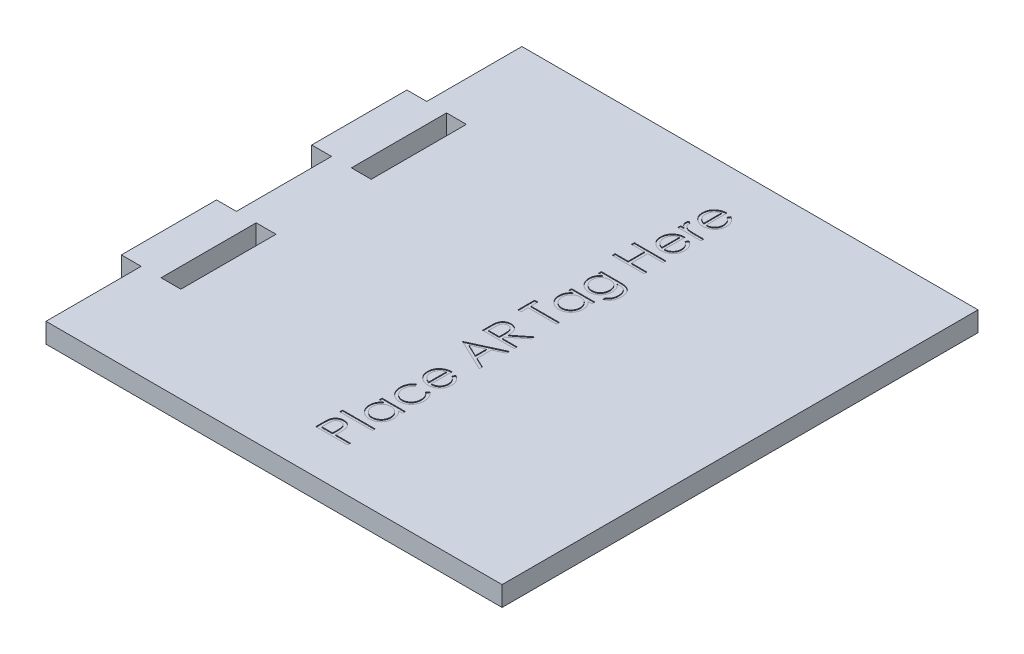
SolidWorks part; units mm, degrees
material "Pine"
ref_plane "Front Plane" through (0, 0, 0) normal (0, 0, 1) x (1, 0, 0)
ref_plane "Top Plane" through (0, 0, 0) normal (0, 1, 0) x (1, 0, 0)
ref_plane "Right Plane" through (0, 0, 0) normal (1, 0, 0) x (0, 0, -1)
sketch "Sketch1" plane through (0, 0, 0) normal (0, 1, 0) x (1, 0, 0)
  line L1 (-76.2, -76.2) -> (76.2, -76.2)
  line L2 (-76.2, -76.2) -> (-76.2, 76.2)
  line L3 (-76.2, 76.2) -> (76.2, 76.2)
  line L4 (76.2, -76.2) -> (76.2, 76.2)
  line L5 (-76.2, -76.2) -> (76.2, 76.2) construction
  line L6 (-76.2, 76.2) -> (76.2, -76.2) construction
  point P0 (0, 0)
  dimension "D1" = 152.4
  dimension "D2" = 152.4
extrude "Boss-Extrude1" add sketch "Sketch1" along normal blind 6.35
sketch "Sketch2" plane through (0, 6.35, 0) normal (0, 1, 0) x (1, 0, 0)
  line L1 (-57.15, -45.72) -> (-63.5, -45.72)
  line L2 (-57.15, -45.72) -> (-57.15, -15.24)
  line L3 (-57.15, -15.24) -> (-63.5, -15.24)
  line L4 (-63.5, -45.72) -> (-63.5, -15.24)
  line L5 (-76.2, -76.2) -> (76.2, -76.2) construction
  line L6 (-57.15, 15.24) -> (-63.5, 15.24)
  line L7 (-57.15, 15.24) -> (-57.15, 45.72)
  line L8 (-57.15, 45.72) -> (-63.5, 45.72)
  line L9 (-63.5, 15.24) -> (-63.5, 45.72)
  line L10 (-76.2, 76.2) -> (-76.2, -76.2) construction
  point P4 (-56.9062, -45.72)
  point P12 (-60.325, 15.24)
  point P13 (0, 0)
  point P14 (0, 0)
  dimension "D1" = 30.48
  dimension "D2" = 30.48
  dimension "D3" = 30.48
  dimension "D4" = 30.48
  dimension "D5" = 6.35
  dimension "D6" = 12.7
extrude "Cut-Extrude1" cut sketch "Sketch2" against normal through all
sketch "Sketch3" plane through (0, 6.35, 0) normal (0, 1, 0) x (1, 0, 0)
  line L0 (-76.2, 76.2) -> (-76.2, -76.2) construction
  line L1 (-76.2, -76.2) -> (-69.85, -76.2)
  line L2 (-76.2, -76.2) -> (-76.2, -45.72)
  line L3 (-76.2, -45.72) -> (-69.85, -45.72)
  line L4 (-69.85, -76.2) -> (-69.85, -45.72)
  line L5 (-76.2, -15.24) -> (-69.85, -15.24)
  line L6 (-76.2, -15.24) -> (-76.2, 15.24)
  line L7 (-76.2, 15.24) -> (-69.85, 15.24)
  line L8 (-69.85, -15.24) -> (-69.85, 15.24)
  line L9 (76.2, 76.2) -> (-76.2, 76.2) construction
  line L10 (-76.2, 45.72) -> (-69.85, 45.72)
  line L11 (-76.2, 45.72) -> (-76.2, 76.2)
  line L12 (-76.2, 76.2) -> (-69.85, 76.2)
  line L13 (-69.85, 45.72) -> (-69.85, 76.2)
  dimension "D1" = 30.48
  dimension "D2" = 30.48
  dimension "D3" = 6.35
extrude "Cut-Extrude2" cut sketch "Sketch3" against normal through all
sketch "Sketch4" plane through (0, 6.35, 0) normal (0, 1, 0) x (1, 0, 0)
  line L0 (12.7, -63.5) -> (12.7, 72.8938) construction
  line L1 (76.2, -76.2) -> (76.2, 76.2) construction
  line L2 (-69.85, -76.2) -> (76.2, -76.2) construction
  text T0 "Place AR Tag Here" font "Century Gothic" height 10.16
  point P5 (19.05, -69.0929)
  point P6 (19.05, 72.8938)
  point P7 (19.05, -59.9912)
  point P8 (19.05, -50.2827)
  point P9 (0, 0)
  point P10 (19.05, -55.1369)
  point P11 (0, 0)
  point P12 (19.05, -58.1708)
  point P13 (0, 0)
  point P14 (0, 0)
  point P15 (19.05, -64.8454)
  point P16 (0, 0)
  dimension "D1" = 63.5
  dimension "D2" = 12.7
extrude "Cut-Extrude3" cut sketch "Sketch4" against normal blind 0.254
